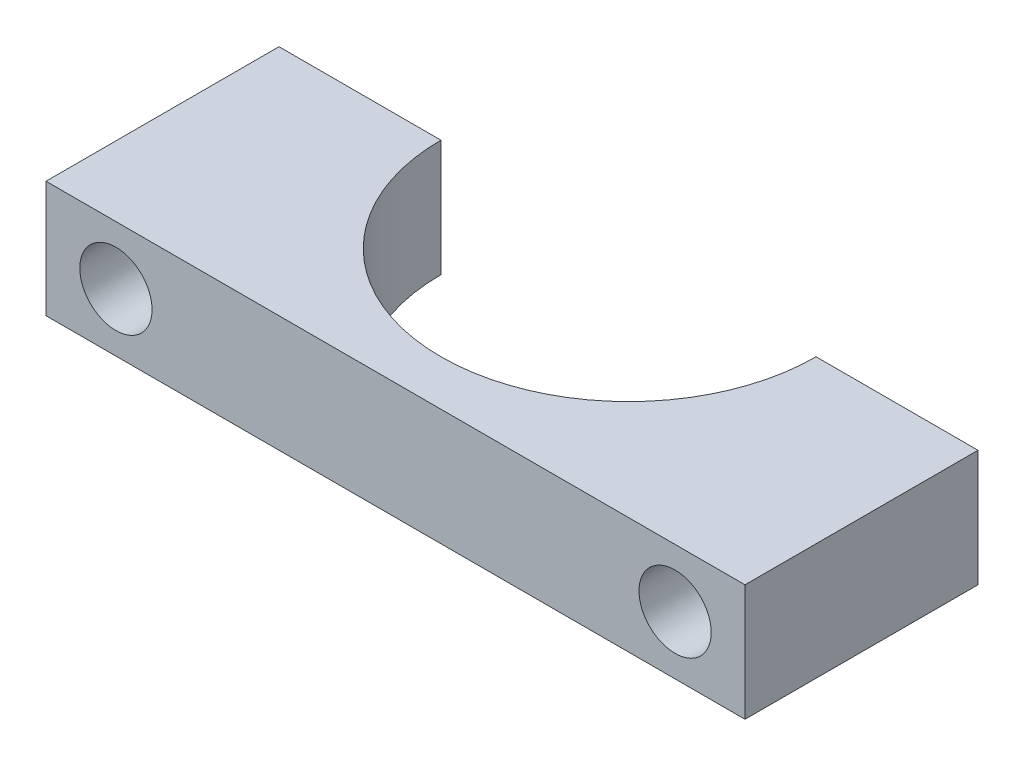
SolidWorks part; units mm, degrees
ref_plane "Front Plane" through (0, 0, 0) normal (0, 0, 1) x (1, 0, 0)
ref_plane "Top Plane" through (0, 0, 0) normal (0, 1, 0) x (1, 0, 0)
ref_plane "Right Plane" through (0, 0, 0) normal (1, 0, 0) x (0, 0, -1)
sketch "Sketch1" plane through (0, 0, 0) normal (0, 1, 0) x (1, 0, 0)
  line L0 (16.1, 0) -> (30, 0)
  line L1 (-30, 0) -> (-16.1, 0)
  line L2 (-30, 0) -> (-30, -20)
  line L3 (-30, -20) -> (30, -20)
  line L4 (30, 0) -> (30, -20)
  arc A0 (-16.1, 0) -> (16.1, 0) centre (0, 0) ccw
  dimension "D4" = 32.2
  dimension "D1" = 60
  dimension "D6" = 20
extrude "Boss-Extrude1" add sketch "Sketch1" along normal blind 10
sketch "Sketch2" plane through (0, 0, 20) normal (0, 0, 1) x (1, 0, 0)
  line L0 (-30, 10) -> (-30, 0) construction
  line L1 (30, 10) -> (30, 0) construction
  line L2 (-30, 0) -> (30, 0) construction
  circle A0 centre (-24, 5) radius 3.1
  circle A1 centre (24, 5) radius 3.1
  dimension "D4" = 6.2
  dimension "D5" = 6.2
  dimension "D1" = 6
  dimension "D2" = 6
  dimension "D3" = 5
  dimension "D6" = 5
extrude "Cut-Extrude1" cut sketch "Sketch2" against normal through all
